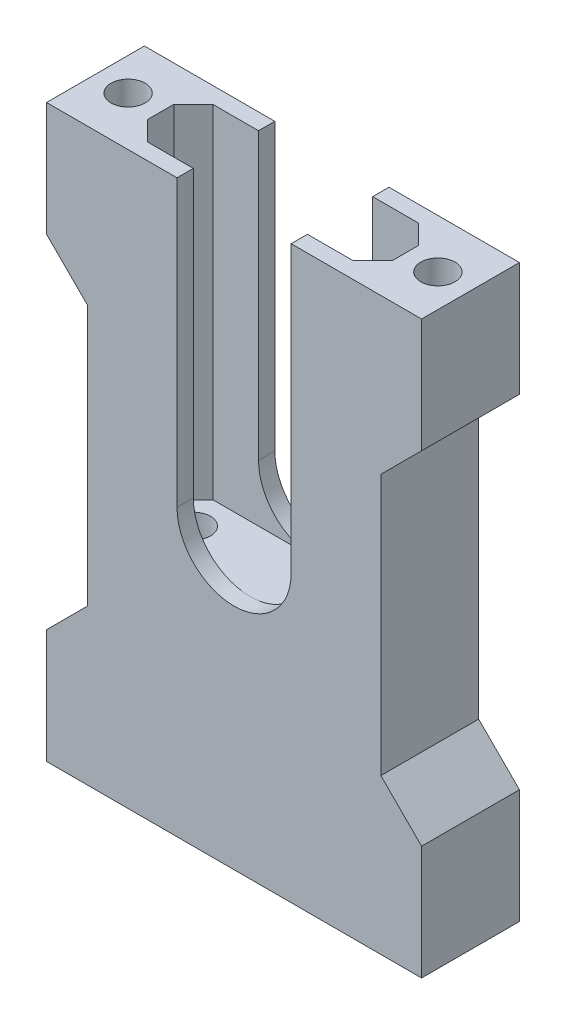
SolidWorks part; units mm, degrees
other "Uwaga1"
sketch "Szkic6" plane through (28, 56, 16) normal (0.3058, 0.389, 0.869) x (0.9408, -0.2636, -0.2131)
sketch "Szkic7" plane through (27, 56, 12) normal (0.3058, 0.389, 0.869) x (0.9408, -0.2636, -0.2131)
sketch "Szkic8" plane through (23, 56, 12) normal (0.3058, 0.389, 0.869) x (0.9408, -0.2636, -0.2131)
sketch "Szkic9" plane through (23, 56, 12) normal (0.3058, 0.389, 0.869) x (0.9408, -0.2636, -0.2131)
sketch "Szkic10" plane through (23, 56, 12) normal (0.3058, 0.389, 0.869) x (0.9408, -0.2636, -0.2131)
material "ABS"
ref_plane "Płaszczyzna przednia" through (0, 0, 0) normal (0, 0, 1) x (1, 0, 0)
ref_plane "Płaszczyzna górna" through (0, 0, 0) normal (0, 1, 0) x (1, 0, 0)
ref_plane "Płaszczyzna prawa" through (0, 0, 0) normal (1, 0, 0) x (0, 0, -1)
sketch "Szkic1" plane through (0, 0, 0) normal (0, 0, 1) x (1, 0, 0)
  line L0 (-23, 0) -> (23, 0)
  line L1 (23, 0) -> (23, 14)
  line L2 (23, 14) -> (18, 19)
  line L3 (18, 19) -> (18, 51)
  line L4 (18, 51) -> (23, 56)
  line L5 (23, 56) -> (23, 70)
  line L7 (-23, 70) -> (-23, 56)
  line L8 (-23, 56) -> (-18, 51)
  line L9 (-18, 51) -> (-18, 19)
  line L10 (-18, 19) -> (-23, 14)
  line L11 (-23, 14) -> (-23, 0)
  line L12 (23, 70) -> (7, 70)
  line L14 (-23, 70) -> (-7, 70)
  line L16 (7, 35) -> (7, 70)
  line L17 (-18, 35) -> (18, 35) construction
  line L18 (-7, 35) -> (-7, 70)
  arc A0 (-7, 35) -> (7, 35) centre (0, 35) ccw
  point P4 (0, 0)
  dimension "D2" = 5
  dimension "D3" = 5
  dimension "D4" = 5
  dimension "D5" = 5
  dimension "D6" = 135
  dimension "D7" = 70
  dimension "D8" = 180
  dimension "D9" = 14
  dimension "D10" = 14
  dimension "D11" = 14
  dimension "D12" = 14
  dimension "D13" = 14
  dimension "D14" = 46
  dimension "D15" = 16
  dimension "D16" = 16
  dimension "D17" = 70
extrude "Dodanie-wyciągnięcie1" add sketch "Szkic1" along normal blind 12
ref_plane "Płaszczyzna1" through (0, 70, 0) normal (0, 1, 0) x (1, 0, 0)
sketch "Szkic2" plane through (0, 70, 0) normal (0, 1, 0) x (1, 0, 0)
  line L0 (0, 0) -> (0, -6) construction
  line L1 (0, -6) -> (-19, -6) construction
  line L2 (0, -6) -> (19, -6) construction
  circle A0 centre (-19, -6) radius 2.1
  circle A1 centre (19, -6) radius 2.1
  dimension "D3" = 4.2
  dimension "D5" = 4.2
  dimension "D1" = 6
  dimension "D2" = 19
  dimension "D4" = 19
extrude "Wytnij-wyciągnięcie1" cut sketch "Szkic2" against normal blind 10
ref_plane "Płaszczyzna2" through (0, 35, 0) normal (0, -1, 0) x (-1, 0, 0)
mirror "Lustro1" about plane through (0, 35, 0) normal (0, -1, 0) of "Wytnij-wyciągnięcie1"
sketch "Szkic3" plane through (0, 70, 0) normal (0, -1, 0) x (-1, 0, 0)
  line L0 (0, 0) -> (0, -6) construction
  line L1 (0, -6) -> (15, -6) construction
  line L2 (15, -10) -> (15, -2) construction
  line L6 (15, -2) -> (12.6, -2) construction
  line L7 (15, -2) -> (15, -4.4) construction
  line L8 (12.6, -2) -> (-12.6, -2)
  line L9 (15, -4.4) -> (12.6, -2)
  line L10 (15, -4.4) -> (15, -7.6)
  line L11 (-15, -4.4) -> (-15, -7.6)
  line L12 (-15, -4.4) -> (-12.6, -2)
  line L13 (-15, -7.6) -> (-12.6, -10)
  line L14 (12.6, -10) -> (-12.6, -10)
  line L15 (15, -7.6) -> (12.6, -10)
  point P7 (15, -6)
  point P13 (0, -2)
  point P14 (-15, -6)
  dimension "D1" = 6
  dimension "D2" = 15
  dimension "D3" = 8
  dimension "D4" = 2.4
  dimension "D5" = 2.4
extrude "Wytnij-wyciągnięcie2" cut sketch "Szkic3" along normal blind 42
sketch "Szkic4" plane through (0, 28, 0) normal (0, 1, 0) x (1, 0, 0)
  line L0 (0, 0) -> (0, -6) construction
  line L1 (-11, -6) -> (11, -6) construction
  circle A0 centre (11, -6) radius 2.1
  circle A1 centre (-11, -6) radius 2.1
  dimension "D3" = 4.2
  dimension "D1" = 6
  dimension "D2" = 11
extrude "Wytnij-wyciągnięcie3" cut sketch "Szkic4" against normal up to next
sketch "Szkic5" plane through (0, 0, 0) normal (0, -1, 0) x (1, 0, 0)
  line L0 (0, -55) -> (0, 55) construction
  line L1 (11, 1.7276) -> (14.7, 3.8638)
  line L2 (14.7, 3.8638) -> (14.7, 8.1362)
  line L3 (14.7, 8.1362) -> (11, 10.2724)
  line L4 (11, 10.2724) -> (7.3, 8.1362)
  line L5 (7.3, 8.1362) -> (7.3, 3.8638)
  line L6 (7.3, 3.8638) -> (11, 1.7276)
  line L7 (-7.3, 3.8638) -> (-11, 1.7276)
  line L8 (-7.3, 8.1362) -> (-7.3, 3.8638)
  line L9 (-11, 10.2724) -> (-7.3, 8.1362)
  line L10 (-14.7, 8.1362) -> (-11, 10.2724)
  line L11 (-14.7, 3.8638) -> (-14.7, 8.1362)
  line L12 (-11, 1.7276) -> (-14.7, 3.8638)
  circle A0 centre (11, 6) radius 3.7 construction
  circle A1 centre (-11, 6) radius 3.7 construction
  dimension "D1" = 7.4
extrude "Wytnij-wyciągnięcie4" cut sketch "Szkic5" against normal blind 6
equation "\"hight\"=70"
equation "\"D10@Szkic1\"=\"InsertHight\""
equation "\"InsertHight\"=14"
equation "\"D9@Szkic1\"=\"InsertHight\""
equation "\"D11@Szkic1\"=\"InsertHight\""
equation "\"D12@Szkic1\"=\"InsertHight\""
equation "\"FazeX\"= 5"
equation "\"D5@Szkic1\"=\"FazeX\""
equation "\"D4@Szkic1\"=\"FazeX\""
equation "\"D2@Szkic1\"=\"FazeX\""
equation "\"D3@Szkic1\"=\"FazeX\""
equation "\"width\"= 46"
equation "\"D15@Szkic1\"=\"TopWidth\""
equation "\"TopWidth\"= 16"
equation "\"D16@Szkic1\"=\"TopWidth\""
equation "\"D7@Szkic1\"=\"hight\""
equation "\"D17@Szkic1\"=\"hight\""
equation "\"depth\"= 12"
equation "\"D1@Szkic2\"=\"depth\"/2"
equation "\"D1@Dodanie-wyciągnięcie1\"=\"depth\""
equation "\"D14@Szkic1\"=\"width\""
equation "\"ToInsertX\"= ( \"width\" - \"TopWidth\" - \"TopWidth\" ) / 2 + ( \"TopWidth\" / 2 ) + \"FazeX\" * 0.8"
equation "\"InsertDiameter\"= 4.2"
equation "\"D3@Szkic2\"=\"InsertDiameter\""
equation "\"D2@Szkic2\"=\"ToInsertX\""
equation "\"D4@Szkic2\"=\"ToInsertX\""
equation "\"D5@Szkic2\"=\"InsertDiameter\""
equation "\"InsertDepth\"=10"
equation "\"D1@Wytnij-wyciągnięcie1\"=\"InsertDepth\""
equation "\"Diameter\"= \"width\" - \"TopWidth\" - \"TopWidth\""
equation "\"D1@Szkic3\"=\"depth\"/2"
equation "\"RailX\"= 8"
equation "\"D2@Szkic3\"=\"Diameter\"/2+\"RailX\""
equation "\"RailZ\"= 8"
equation "\"D3@Szkic3\"=\"RailZ\""
equation "\"D1@Wytnij-wyciągnięcie2\"=\"hight\"/2+\"Diameter\"/2"
equation "\"D4@Szkic3\" = \"RailZ\" * 0.3"
equation "\"D5@Szkic3\" = \"RailZ\" * 0.3"
equation "\"D1@Szkic4\"=\"depth\"/2"
equation "\"D2@Szkic4\"=\"Diameter\"/2+\"RailX\"/2"
